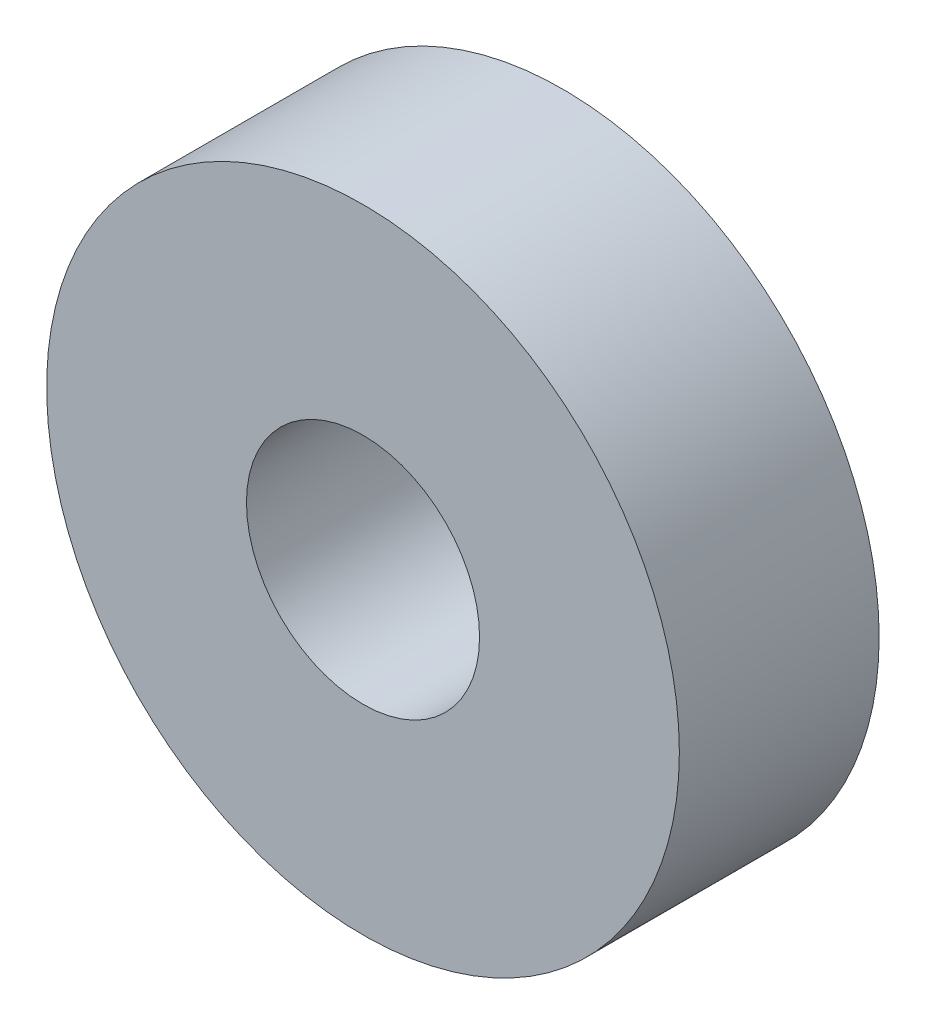
SolidWorks part; units mm, degrees
ref_plane "Plan de face" through (0, 0, 0) normal (0, 0, 1) x (1, 0, 0)
ref_plane "Plan de dessus" through (0, 0, 0) normal (0, 1, 0) x (1, 0, 0)
ref_plane "Plan de droite" through (0, 0, 0) normal (1, 0, 0) x (0, 0, -1)
sketch "Esquisse1" plane through (0, 0, 0) normal (0, 0, 1) x (1, 0, 0)
  circle A0 centre (0, 0) radius 3.5
  circle A1 centre (0, 0) radius 9.5
  dimension "D1" = 7
  dimension "D2" = 19
extrude "Boss.-Extru.1" add sketch "Esquisse1" along normal blind 6
